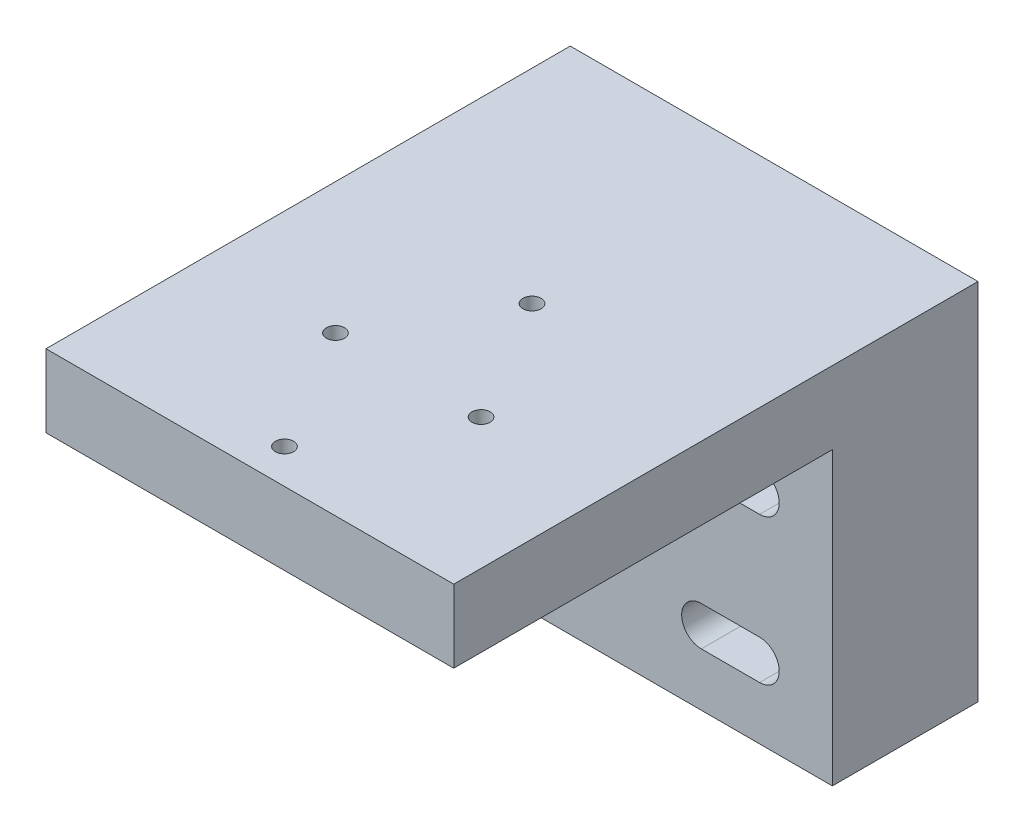
SolidWorks part; units mm, degrees
material "铝材"
ref_plane "前基準面" through (0, 0, 0) normal (0, 0, 1) x (1, 0, 0)
ref_plane "上基準面" through (0, 0, 0) normal (0, 1, 0) x (1, 0, 0)
ref_plane "右基準面" through (0, 0, 0) normal (1, 0, 0) x (0, 0, -1)
sketch "草图1" plane through (0, 0, 0) normal (0, 0, 1) x (1, 0, 0)
  line L1 (0, 0) -> (56, 0)
  line L2 (0, 0) -> (0, 50)
  line L3 (0, 50) -> (56, 50)
  line L4 (56, 0) -> (56, 50)
  dimension "D1" = 56
  dimension "D2" = 50
extrude "凸台-拉伸1" add sketch "草图1" along normal blind 72
sketch "草图2" plane through (56, 0, 0) normal (1, 0, 0) x (0, 0, -1)
  line L0 (-72, 50) -> (0, 50) construction
  line L1 (-72, 0) -> (-20, 0)
  line L2 (-72, 0) -> (-72, 40)
  line L3 (-72, 40) -> (-20, 40)
  line L4 (-20, 0) -> (-20, 40)
  line L5 (0, 0) -> (0, 50) construction
  dimension "D1" = 10
  dimension "D2" = 20
extrude "切除-拉伸1" cut sketch "草图2" against normal through all
hole_wizard "M3 螺纹孔1" positions "草图4" profile "草图3" tap size "M3" standard "ISO"
sketch "草图4" plane through (0, 50, 0) normal (0, 1, 0) x (-1, 0, 0)
  point P0 (-28, 67.25)
  point P1 (-28, 33.25)
  point P4 (-18, 50.25)
  point P7 (-38, 50.25)
sketch "草图3" plane through (28, 50, 67.25) normal (1, 0, 0) x (0, 0, 1)
  line L0 (0, 0) -> (0, 8.2511)
  line L1 (0, 8.2511) -> (1.25, 7.5)
  line L2 (1.25, 7.5) -> (1.25, 0)
  line L5 (1.25, 0) -> (0, 0)
  line L10 (0, 8.2511) -> (-1.25, 7.5) construction
  line L11 (0, -6.35) -> (0, 107.95) construction
  dimension "螺纹孔钻头直径" = 2.5
  dimension "螺纹孔钻头深度" = 7.5
  dimension "导头角度" = 118
cosmetic thread "孔螺蚊线1" parameters "D1"=6, "D2"=3
cosmetic thread "孔螺蚊线2" parameters "D1"=6, "D2"=3
cosmetic thread "孔螺蚊线3" parameters "D1"=6, "D2"=3
cosmetic thread "孔螺蚊线4" parameters "D1"=6, "D2"=3
sketch "草图5" plane through (0, 0, 20) normal (0, 0, 1) x (1, 0, 0)
  line L0 (10, 30) -> (18, 30) construction
  line L1 (10, 32.7) -> (18, 32.7)
  line L2 (10, 27.3) -> (18, 27.3)
  line L3 (28, 0) -> (28, 40) construction
  line L4 (0, 0) -> (56, 0) construction
  line L5 (0, 40) -> (56, 40) construction
  line L6 (0, 20) -> (56, 20) construction
  line L7 (0, 0) -> (0, 40) construction
  line L8 (56, 0) -> (56, 40) construction
  line L9 (46, 30) -> (38, 30) construction
  line L10 (46, 32.7) -> (38, 32.7)
  line L11 (46, 27.3) -> (38, 27.3)
  line L12 (10, 10) -> (18, 10) construction
  line L13 (10, 7.3) -> (18, 7.3)
  line L14 (10, 12.7) -> (18, 12.7)
  line L15 (46, 10) -> (38, 10) construction
  line L16 (46, 7.3) -> (38, 7.3)
  line L17 (46, 12.7) -> (38, 12.7)
  arc A0 (10, 32.7) -> (10, 27.3) centre (10, 30) ccw
  arc A1 (18, 27.3) -> (18, 32.7) centre (18, 30) ccw
  arc A2 (46, 32.7) -> (46, 27.3) centre (46, 30) cw
  arc A3 (38, 27.3) -> (38, 32.7) centre (38, 30) cw
  arc A4 (10, 7.3) -> (10, 12.7) centre (10, 10) cw
  arc A5 (18, 12.7) -> (18, 7.3) centre (18, 10) cw
  arc A6 (46, 7.3) -> (46, 12.7) centre (46, 10) ccw
  arc A7 (38, 12.7) -> (38, 7.3) centre (38, 10) ccw
  point P2 (14, 30)
  point P21 (42, 30)
  point P28 (14, 10)
  point P35 (42, 10)
  dimension "D4" = 20
  dimension "D1" = 8
  dimension "D2" = 5.4
  dimension "D3" = 20
extrude "切除-拉伸2" cut sketch "草图5" against normal through all
